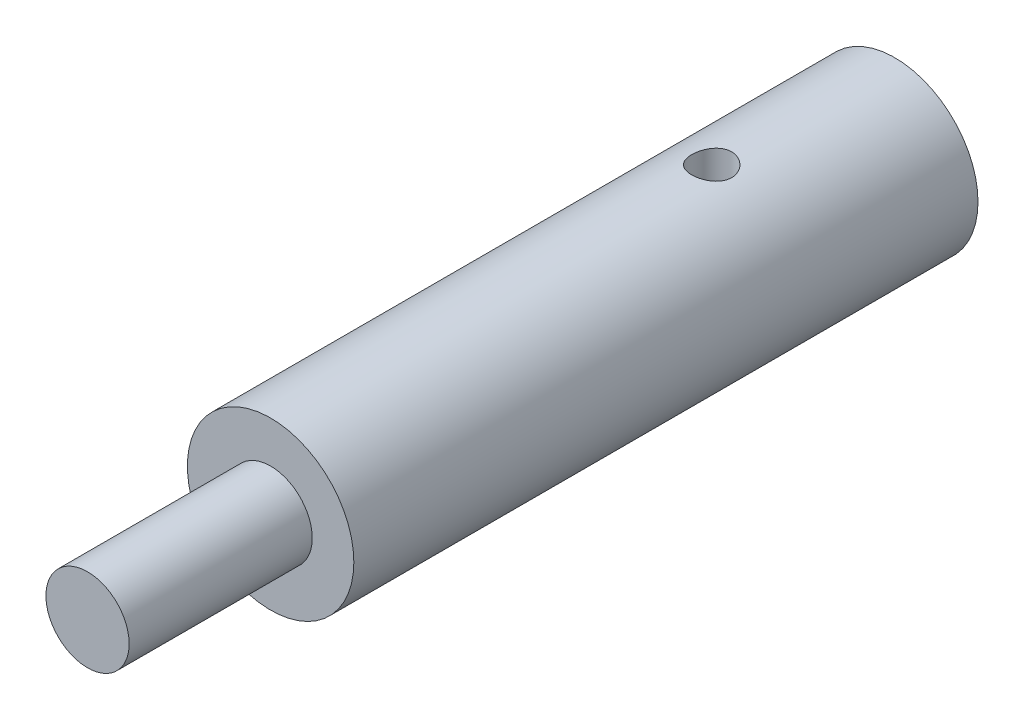
SolidWorks part; units mm, degrees
ref_plane "Front Plane" through (0, 0, 0) normal (0, 0, 1) x (1, 0, 0)
ref_plane "Top Plane" through (0, 0, 0) normal (0, 1, 0) x (1, 0, 0)
ref_plane "Right Plane" through (0, 0, 0) normal (1, 0, 0) x (0, 0, -1)
sketch "Sketch1" plane through (0, 0, 0) normal (1, 0, 0) x (0, 0, -1)
  line L0 (0, 0) -> (97, 0)
  line L1 (97, 0) -> (97, 10)
  line L2 (97, 10) -> (22, 10)
  line L3 (22, 10) -> (22, 5)
  line L4 (22, 5) -> (0, 5)
  line L5 (0, 5) -> (0, 0)
  dimension "D1" = 97
  dimension "D2" = 22
  dimension "D3" = 5
  dimension "D4" = 10
revolve "Revolve1" add sketch "Sketch1" angle 360 about L0
sketch "Sketch2" plane through (0, 0, 0) normal (0, 1, 0) x (1, 0, 0)
  circle A0 centre (0, 75) radius 2.4
  dimension "D2" = 4.8
  dimension "D1" = 75
extrude "Cut-Extrude1" cut sketch "Sketch2" against normal mid plane 20
